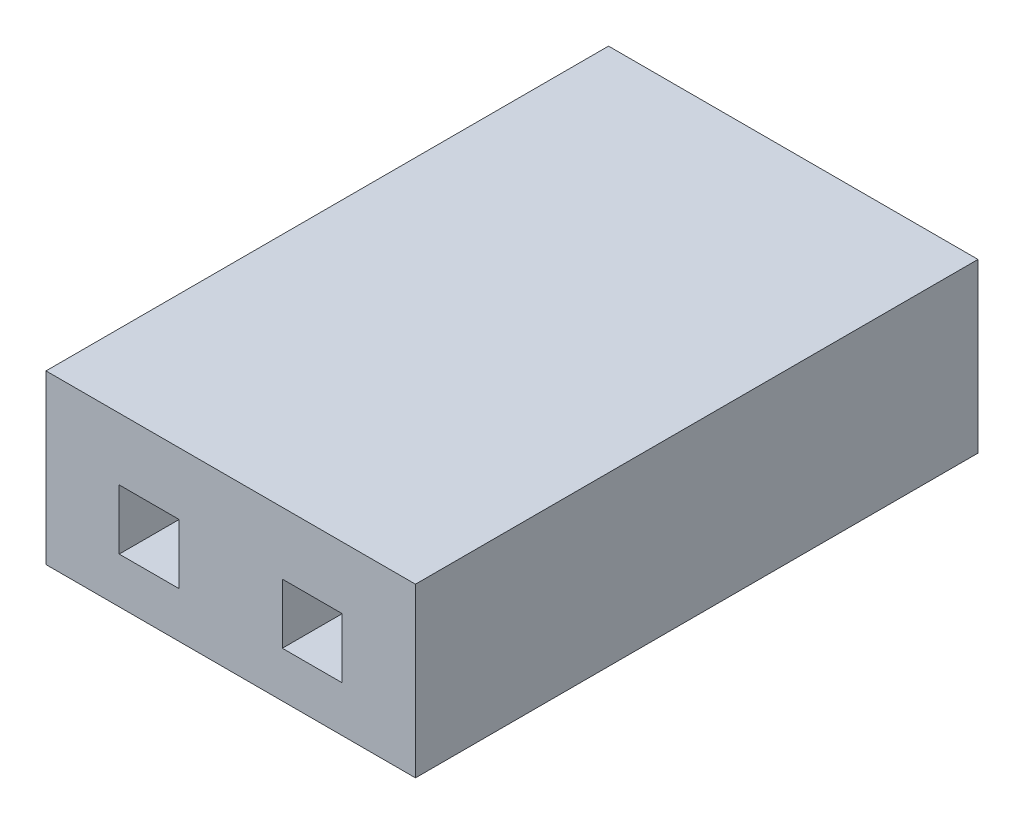
SolidWorks part; units mm, degrees
ref_plane "Přední rovina" through (0, 0, 0) normal (0, 0, 1) x (1, 0, 0)
ref_plane "Horní rovina" through (0, 0, 0) normal (0, 1, 0) x (1, 0, 0)
ref_plane "Pravá rovina" through (0, 0, 0) normal (1, 0, 0) x (0, 0, -1)
sketch "Skica1" plane through (0, 0, 0) normal (0, 0, 1) x (1, 0, 0)
  line L1 (-2.775, -1.26) -> (2.775, -1.26)
  line L2 (-2.775, -1.26) -> (-2.775, 1.26)
  line L3 (-2.775, 1.26) -> (2.775, 1.26)
  line L4 (2.775, -1.26) -> (2.775, 1.26)
  line L5 (-2.775, -1.26) -> (2.775, 1.26) construction
  line L6 (-2.775, 1.26) -> (2.775, -1.26) construction
  point P0 (0, 0)
  dimension "D1" = 5.55
  dimension "D2" = 2.52
extrude "Přidat vysunutím1" add sketch "Skica1" along normal blind 8.45
sketch "Skica2" plane through (0, 0, 8.45) normal (0, 0, 1) x (1, 0, 0)
  line L0 (-2.775, 1.26) -> (-2.775, -1.26) construction
  line L1 (0.775, -0.5734) -> (1.675, -0.5734)
  line L2 (0.775, -0.5734) -> (0.775, 0.3266)
  line L3 (0.775, 0.3266) -> (1.675, 0.3266)
  line L4 (1.675, -0.5734) -> (1.675, 0.3266)
  line L5 (0.775, -0.5734) -> (1.675, 0.3266) construction
  line L6 (0.775, 0.3266) -> (1.675, -0.5734) construction
  line L7 (-1.675, -0.5734) -> (-0.775, -0.5734)
  line L8 (-1.675, -0.5734) -> (-1.675, 0.3266)
  line L9 (-1.675, 0.3266) -> (-0.775, 0.3266)
  line L10 (-0.775, -0.5734) -> (-0.775, 0.3266)
  line L11 (-1.675, -0.5734) -> (-0.775, 0.3266) construction
  line L12 (-1.675, 0.3266) -> (-0.775, -0.5734) construction
  line L13 (2.775, -1.26) -> (2.775, 1.26) construction
  point P0 (1.225, -0.1234)
  point P5 (-1.225, -0.1234)
  dimension "D1" = 0.9
  dimension "D2" = 0.9
  dimension "D3" = 1.1
  dimension "D4" = 1.1
extrude "Odebrat vysunutím1" cut sketch "Skica2" against normal blind 7.4323
